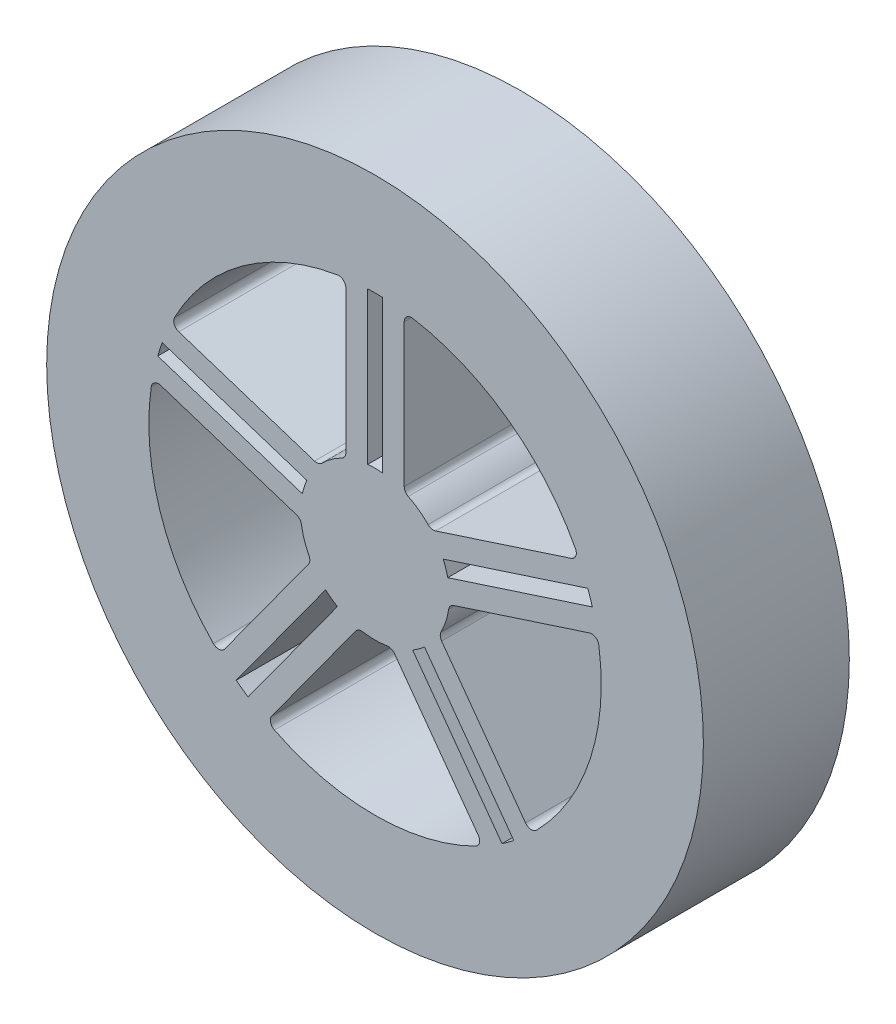
SolidWorks part; units mm, degrees
ref_plane "Plan de face" through (0, 0, 0) normal (0, 0, 1) x (1, 0, 0)
ref_plane "Plan de dessus" through (0, 0, 0) normal (0, 1, 0) x (1, 0, 0)
ref_plane "Plan de droite" through (0, 0, 0) normal (1, 0, 0) x (0, 0, -1)
sketch "Esquisse1" plane through (0, 0, 0) normal (0, 0, 1) x (1, 0, 0)
  circle A1 centre (0, 0) radius 2.1
  circle A2 centre (0, 0) radius 5.1
  dimension "D1" = 4.2
  dimension "D2" = 10.2
  dimension "D3" = 3
extrude "Boss.-Extru.1" add sketch "Esquisse1" along normal blind 10
sketch "Esquisse2" plane through (0, 0, 10) normal (0, 0, 1) x (1, 0, 0)
  line L0 (0, 0) -> (0, 5.1)
  line L1 (0, 5.1) -> (0, 3.4754)
  line L2 (0, 3.4754) -> (2, 3.4754)
  line L3 (2, 3.4754) -> (0, 3.4754)
  line L4 (0, 3.4754) -> (-2, 3.4754)
  line L6 (-2, 3.4754) -> (2, 3.4754)
  line L7 (-2, 3.4754) -> (-2, 16)
  line L8 (-2, 16) -> (2, 16)
  line L9 (2, 3.4754) -> (2, 16)
  line L10 (0, 3.4754) -> (0.5, 3.4754)
  line L11 (0, 3.4754) -> (0, 16)
  line L12 (0, 16) -> (0.5, 16)
  line L13 (0.5, 3.4754) -> (0.5, 16)
  line L14 (0, 16) -> (-0.5, 16)
  line L15 (0, 16) -> (0, 3.4754)
  line L16 (0, 3.4754) -> (-0.5, 3.4754)
  line L17 (-0.5, 16) -> (-0.5, 3.4754)
  circle A0 centre (0, 0) radius 5.1
  circle A1 centre (0, 0) radius 22.5
  circle A2 centre (0, 0) radius 15.5
  spline S0 degree 1 poles (-2, 4.9542) (-2, 16) knots 0 0 1 1
  dimension "D5" = 45
  dimension "D6" = 7
  dimension "D9" = 10.2
  dimension "D1" = 2
  dimension "D2" = 2
  dimension "D3" = 4
  dimension "D4" = 16
  dimension "D7" = 0.5
  dimension "D8" = 0.5
extrude "Boss.-Extru.3" add sketch "Esquisse2" along normal blind 10
fillet "Congé5" radius 0.5 4 edges at (2, 15.3704, 15) (-2, 15.3704, 15) (-2, 4.6915, 15) (2, 4.6915, 15)
pattern_circular "Répétition circulaire2" count 5 over 360 about axis through (0, 0, 0) along (0, 0, 1) of "Boss.-Extru.3"
fillet "Congé6" radius 0.5 16 edges at (-14.0001, 6.6518, 15) (-15.2362, 2.8476, 15) (-10.6525, -11.2594, 15) (-7.4165, -13.6105, 15) (7.4165, -13.6105, 15) (10.6525, -11.2594, 15) (15.2362, 2.8476, 15) (14.0001, 6.6518, 15) (3.8438, 3.3519, 15) (-3.8438, 3.3519, 15) (-5.0799, -0.4524, 15) (-4.3756, -2.6199, 15) (-1.1395, -4.9711, 15) (1.1395, -4.9711, 15) (4.3756, -2.6199, 15) (5.0799, -0.4524, 15)
